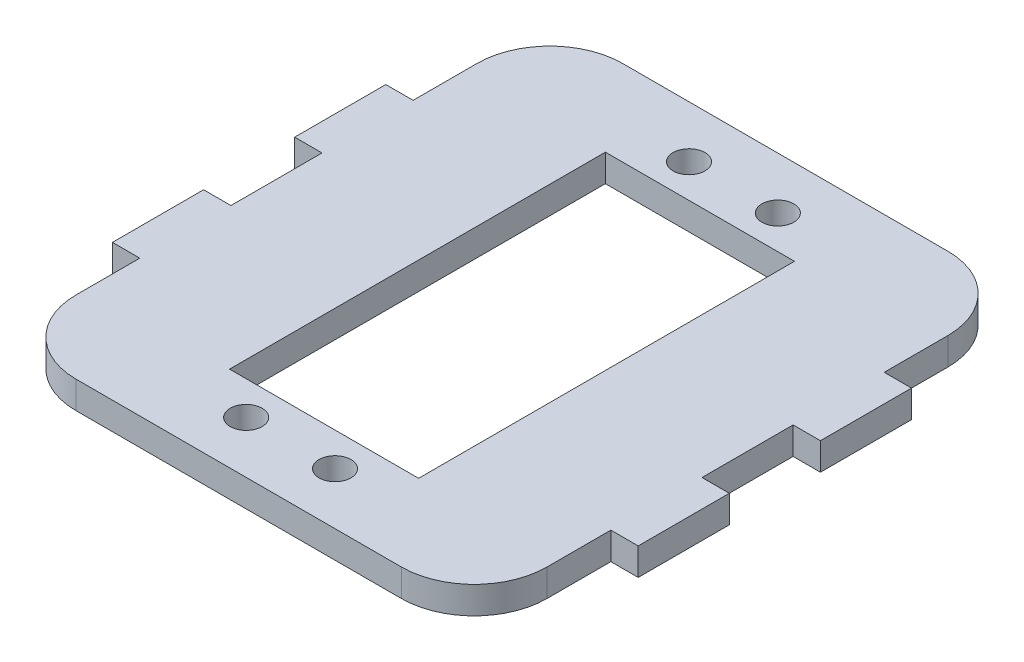
SolidWorks part; units mm, degrees
ref_plane "前视基准面" through (0, 0, 0) normal (0, 0, 1) x (1, 0, 0)
ref_plane "上视基准面" through (0, 0, 0) normal (0, 1, 0) x (1, 0, 0)
ref_plane "右视基准面" through (0, 0, 0) normal (1, 0, 0) x (0, 0, -1)
sketch "草图1" plane through (0, 0, 0) normal (0, 1, 0) x (1, 0, 0)
  line L0 (-426.4128, 0) -> (20894.2285, 0) construction
  line L1 (0, -426.4128) -> (0, 20894.2285) construction
  line L2 (25.85, -30) -> (-25.85, -30)
  line L3 (-25.85, -30) -> (-25.85, -15)
  line L4 (25.85, 30) -> (-25.85, 30)
  line L5 (25.85, -30) -> (25.85, -15)
  line L6 (-10.375, 20.625) -> (-10.375, -20.625)
  line L7 (-10.375, -20.625) -> (10.375, -20.625)
  line L8 (-10.375, 20.625) -> (10.375, 20.625)
  line L9 (10.375, 20.625) -> (10.375, -20.625)
  line L10 (-25.85, -15) -> (-28.85, -15)
  line L11 (-28.85, -15) -> (-28.85, -5)
  line L12 (-28.85, -5) -> (-25.85, -5)
  line L13 (-28.85, 5) -> (-25.85, 5)
  line L14 (-28.85, 15) -> (-28.85, 5)
  line L15 (-25.85, 15) -> (-28.85, 15)
  line L16 (25.85, 15) -> (28.85, 15)
  line L17 (28.85, 15) -> (28.85, 5)
  line L18 (28.85, 5) -> (25.85, 5)
  line L19 (28.85, -5) -> (25.85, -5)
  line L20 (28.85, -15) -> (28.85, -5)
  line L21 (25.85, -15) -> (28.85, -15)
  line L22 (-25.85, -5) -> (-25.85, 5)
  line L23 (-25.85, 15) -> (-25.85, 30)
  line L24 (25.85, -5) -> (25.85, 5)
  line L25 (25.85, 15) -> (25.85, 30)
  circle A0 centre (-4.875, -24.3) radius 1.75
  circle A1 centre (4.875, -24.3) radius 1.75
  circle A2 centre (4.875, 24.3) radius 1.75
  circle A3 centre (-4.875, 24.3) radius 1.75
  point P4 (25.85, 0)
  point P9 (-25.85, 0)
  point P11 (0, 30)
  point P12 (0, -30)
  point P16 (10.375, 0)
  point P18 (-10.375, 0)
  point P19 (0, 20.625)
  point P20 (0, -20.625)
  dimension "D5" = 3.5
  dimension "D1" = 60
  dimension "D2" = 51.7
  dimension "D3" = 41.25
  dimension "D4" = 20.75
  dimension "D6" = 9.75
  dimension "D7" = 48.6
  dimension "D8" = 10
  dimension "D9" = 10
  dimension "D10" = 3
extrude "凸台-拉伸1" add sketch "草图1" along normal blind 3
fillet "圆角1" radius 8 4 edges at (25.85, 1.5, 30) (-25.85, 1.5, 30) (-25.85, 1.5, -30) (25.85, 1.5, -30)
